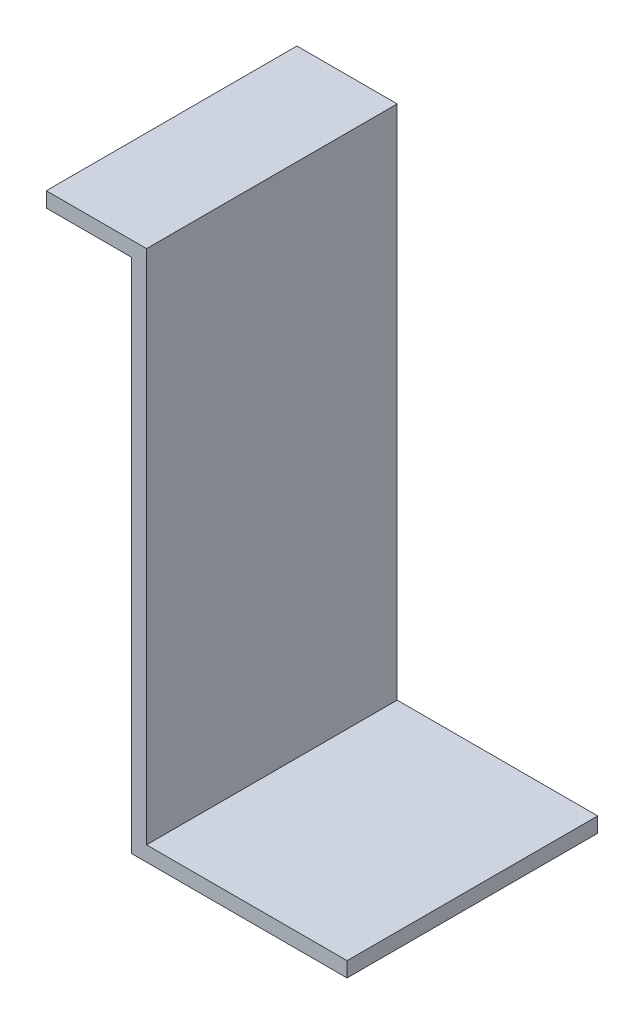
SolidWorks part; units mm, degrees
ref_plane "前视" through (0, 0, 0) normal (0, 0, 1) x (1, 0, 0)
ref_plane "上视" through (0, 0, 0) normal (0, 1, 0) x (1, 0, 0)
ref_plane "右视" through (0, 0, 0) normal (1, 0, 0) x (0, 0, -1)
sketch "Sketch1" plane through (0, 0, 0) normal (0, 1, 0) x (1, 0, 0)
  line L1 (0, 0) -> (43, 0)
  line L2 (0, 0) -> (0, 50)
  line L3 (0, 50) -> (43, 50)
  line L4 (43, 0) -> (43, 50)
  dimension "D1" = 43
  dimension "D2" = 50
extrude "Extrude1" add sketch "Sketch1" along normal blind 3
sketch "Sketch2" plane through (0, 3, 0) normal (0, 1, 0) x (1, 0, 0)
  line L0 (43, 50) -> (0, 50) construction
  line L1 (0, 0) -> (3, 0)
  line L2 (0, 0) -> (0, 50)
  line L3 (0, 50) -> (3, 50)
  line L4 (3, 0) -> (3, 50)
  dimension "D1" = 3
extrude "Extrude2" add sketch "Sketch2" along normal blind 100
sketch "Sketch3" plane through (0, 103, 0) normal (0, 1, 0) x (1, 0, 0)
  line L1 (3, 50) -> (-17, 50)
  line L2 (3, 50) -> (3, 0)
  line L3 (3, 0) -> (-17, 0)
  line L4 (-17, 50) -> (-17, 0)
  dimension "D1" = 20
extrude "Extrude3" add sketch "Sketch3" along normal blind 3
